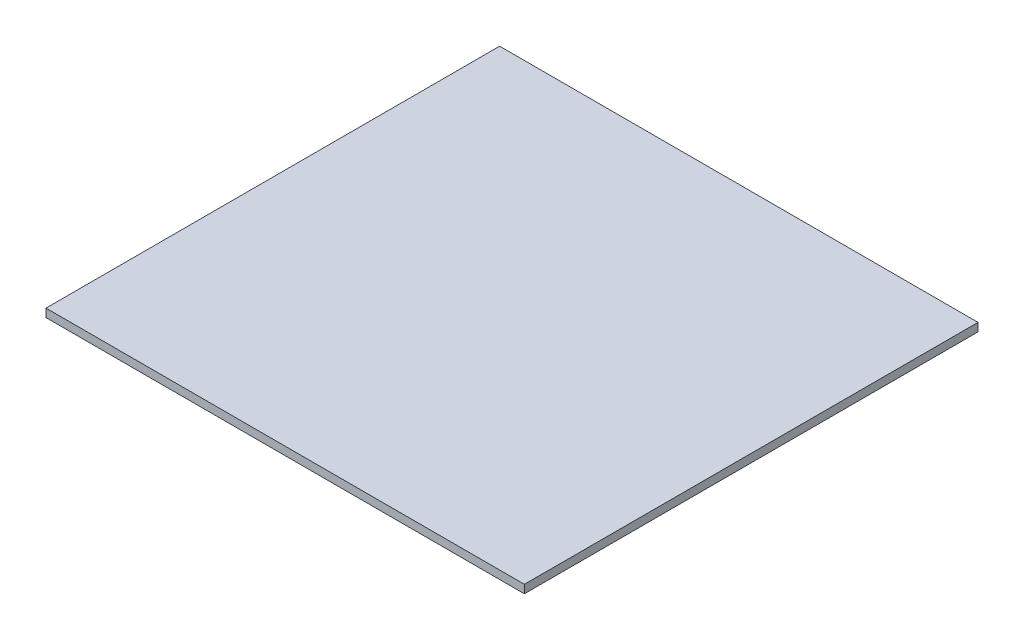
SolidWorks part; units mm, degrees
ref_plane "Front Plane" through (0, 0, 0) normal (0, 0, 1) x (1, 0, 0)
ref_plane "Top Plane" through (0, 0, 0) normal (0, 1, 0) x (1, 0, 0)
ref_plane "Right Plane" through (0, 0, 0) normal (1, 0, 0) x (0, 0, -1)
other "Configuration Table"
sketch "Sketch1" plane through (0, 0, 0) normal (0, 0, 1) x (1, 0, 0)
  line L1 (60, 330) -> (640, 330)
  line L2 (60, 330) -> (60, 340)
  line L3 (60, 340) -> (640, 340)
  line L4 (640, 330) -> (640, 340)
extrude "OVEN_kesme_zemin_plakasi_1" add sketch "Sketch1" against normal blind 550 from offset 30 separate body
